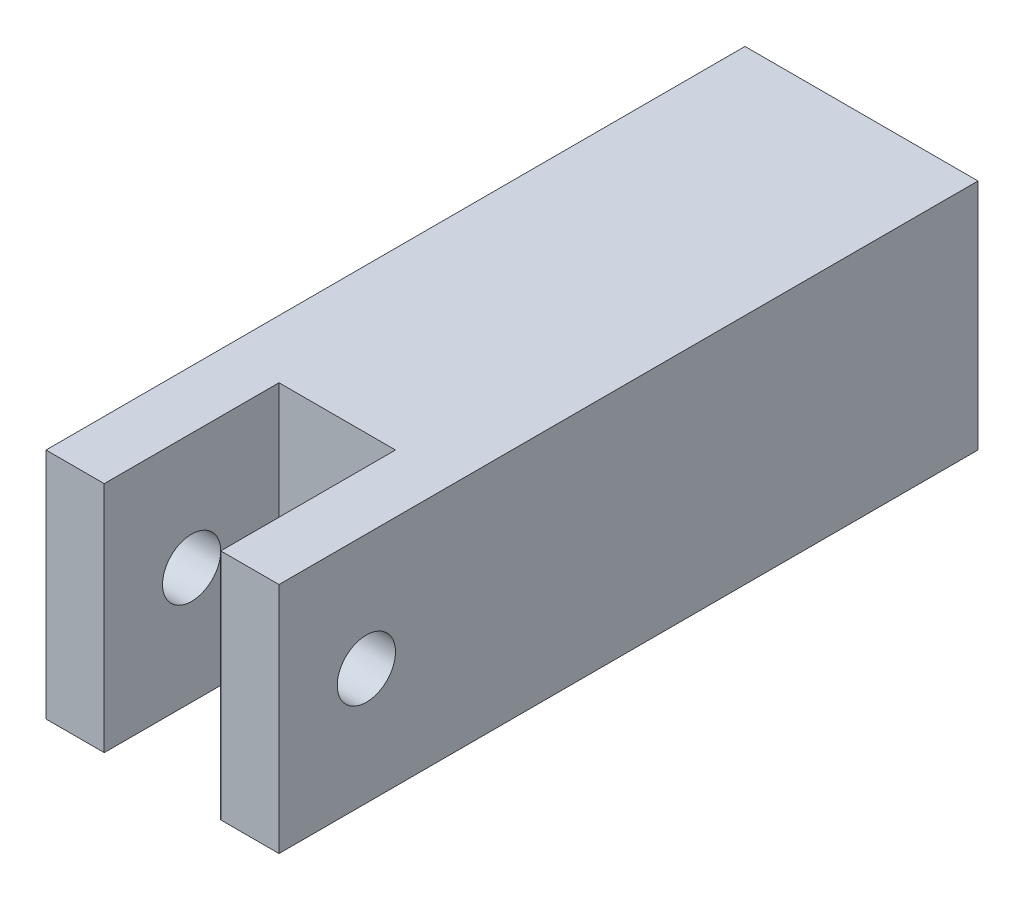
SolidWorks part; units mm, degrees
ref_plane "Přední rovina" through (0, 0, 0) normal (0, 0, 1) x (1, 0, 0)
ref_plane "Horní rovina" through (0, 0, 0) normal (0, 1, 0) x (1, 0, 0)
ref_plane "Pravá rovina" through (0, 0, 0) normal (1, 0, 0) x (0, 0, -1)
sketch "Skica1" plane through (0, 0, 0) normal (0, 0, 1) x (1, 0, 0)
  line L1 (-20, 20) -> (20, 20)
  line L2 (-20, 20) -> (-20, -20)
  line L3 (-20, -20) -> (20, -20)
  line L4 (20, 20) -> (20, -20)
  line L5 (-20, 20) -> (20, -20) construction
  line L6 (-20, -20) -> (20, 20) construction
  point P0 (0, 0)
  dimension "D1" = 40
  dimension "D2" = 40
extrude "Přidat vysunutím1" add sketch "Skica1" along normal blind 90
sketch "Skica3" plane through (0, 0, 90) normal (0, 0, 1) x (1, 0, 0)
  line L0 (20, 20) -> (-20, 20) construction
  line L1 (20, -20) -> (10, -20)
  line L2 (20, -20) -> (20, 20)
  line L3 (20, 20) -> (10, 20)
  line L4 (10, -20) -> (10, 20)
  line L6 (-20, -20) -> (-10, -20)
  line L7 (-20, -20) -> (-20, 20)
  line L8 (-20, 20) -> (-10, 20)
  line L9 (-10, -20) -> (-10, 20)
  dimension "D1" = 20
  dimension "D2" = 10
extrude "Přidat vysunutím2" add sketch "Skica3" along normal blind 30
sketch "Skica4" plane through (-20, 0, 0) normal (-1, 0, 0) x (0, 0, 1)
  line L0 (120, 20) -> (120, -20) construction
  line L1 (120, 20) -> (0, 20) construction
  circle A0 centre (105, 0) radius 5
  dimension "D1" = 10
  dimension "D2" = 15
  dimension "D3" = 20
extrude "Odebrat vysunutím1" cut sketch "Skica4" against normal blind 40
sketch "Skica5" plane through (0, 0, 0) normal (0, 0, -1) x (-1, 0, 0)
  circle A0 centre (0, 0) radius 2.5
  dimension "D1" = 5
extrude "Odebrat vysunutím2" cut sketch "Skica5" against normal blind 10
